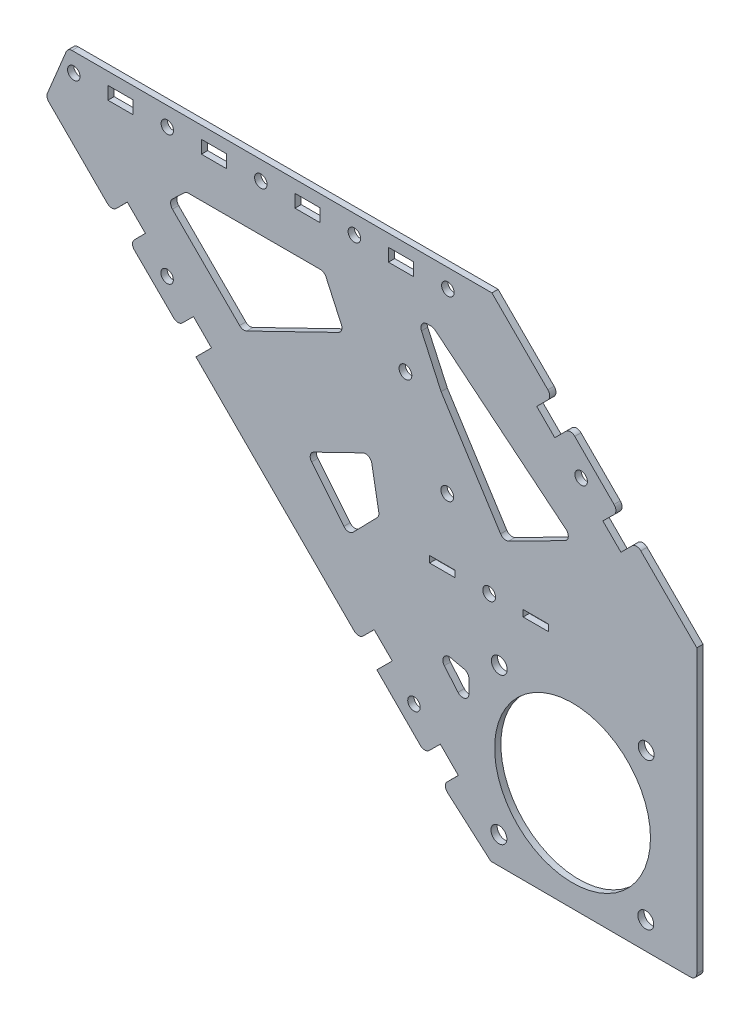
SolidWorks part; units mm, degrees
ref_plane "前视基准面" through (0, 0, 0) normal (0, 0, 1) x (1, 0, 0)
ref_plane "上视基准面" through (0, 0, 0) normal (0, 1, 0) x (1, 0, 0)
ref_plane "右视基准面" through (0, 0, 0) normal (1, 0, 0) x (0, 0, -1)
sketch "草图1" plane through (0, 0, 0) normal (0, 0, 1) x (1, 0, 0)
  line L261 (47.0274, 35.0547) -> (47.0274, 14.9275) construction
  line L315 (7.0453, -5.1539) -> (20.7932, -17.1527)
  line L316 (-52.9726, 134.9275) -> (-52.9726, 126.7057) construction
  line L332 (-112.9726, 134.9275) -> (-97.9726, 134.9275) construction
  line L334 (-42.0226, 136.9925) -> (-33.9226, 136.9925)
  line L335 (-42.0226, 136.9925) -> (-42.0226, 132.8625)
  line L336 (-42.0226, 132.8625) -> (-33.9226, 132.8625)
  line L337 (-33.9226, 136.9925) -> (-33.9226, 132.8625)
  line L338 (-42.0226, 136.9925) -> (-33.9226, 132.8625) construction
  line L339 (-42.0226, 132.8625) -> (-33.9226, 136.9925) construction
  line L389 (-114.8842, 140.9275) -> (21.1546, 140.9275)
  line L390 (-22.9726, 134.9275) -> (-22.9726, 144.5851) construction
  line L395 (-37.9726, 134.9275) -> (-7.9726, 134.9275) construction
  line L418 (86.9005, 75.1817) -> (21.1546, 140.9275) construction
  line L419 (-3.9226, 132.8625) -> (-12.0226, 136.9925) construction
  line L420 (-3.9226, 136.9925) -> (-12.0226, 132.8625) construction
  line L421 (7.0274, 134.9275) -> (-7.9726, 134.9275) construction
  line L422 (-12.0226, 136.9925) -> (-12.0226, 132.8625)
  line L423 (-3.9226, 132.8625) -> (-12.0226, 132.8625)
  line L424 (-3.9226, 136.9925) -> (-3.9226, 132.8625)
  line L443 (-3.9226, 136.9925) -> (-12.0226, 136.9925)
  line L444 (-102.0226, 136.9925) -> (-93.9226, 132.8625) construction
  line L445 (-102.0226, 132.8625) -> (-93.9226, 136.9925) construction
  line L447 (-67.9726, 134.9275) -> (-97.9726, 134.9275) construction
  line L448 (-104.2577, 114.6407) -> (-83.0445, 93.4275) construction
  line L449 (-63.9226, 132.8625) -> (-72.0226, 136.9925) construction
  line L483 (-63.9226, 136.9925) -> (-72.0226, 132.8625) construction
  line L515 (47.0274, 35.0547) -> (47.0274, 134.9275) construction
  line L516 (47.0274, 134.9275) -> (-52.9726, 134.9275) construction
  line L517 (-102.0226, 136.9925) -> (-93.9226, 136.9925)
  line L518 (-102.0226, 136.9925) -> (-102.0226, 132.8625)
  line L519 (-102.0226, 132.8625) -> (-93.9226, 132.8625)
  line L520 (-93.9226, 136.9925) -> (-93.9226, 132.8625)
  line L521 (-72.0226, 136.9925) -> (-72.0226, 132.8625)
  line L522 (-63.9226, 132.8625) -> (-72.0226, 132.8625)
  line L523 (-63.9226, 136.9925) -> (-63.9226, 132.8625)
  line L524 (-63.9226, 136.9925) -> (-72.0226, 136.9925)
  line L556 (21.4033, 132.1936) -> (81.3921, 72.2048) construction
  line L557 (54.0276, 108.0546) -> (35.0675, 89.0945) construction
  line L558 (42.8199, 112.2619) -> (35.5367, 116.5752) construction
  line L559 (56.7499, 95.3621) -> (62.5482, 89.5638)
  line L576 (56.7499, 95.3621) -> (58.2348, 96.847)
  line L577 (58.2348, 96.847) -> (64.0331, 91.0487) construction
  line L578 (62.5482, 89.5638) -> (64.0331, 91.0487)
  line L579 (56.7499, 95.3621) -> (64.0331, 91.0487) construction
  line L580 (58.2348, 96.847) -> (62.5482, 89.5638) construction
  line L581 (41.335, 110.777) -> (37.0216, 118.0602) construction
  line L582 (35.5367, 116.5752) -> (37.0216, 118.0602)
  line L583 (42.8199, 112.2619) -> (37.0216, 118.0602) construction
  line L584 (41.335, 110.777) -> (42.8199, 112.2619)
  line L585 (41.335, 110.777) -> (35.5367, 116.5752)
  line L586 (60.3915, 93.2054) -> (59.649, 92.4629) construction
  line L587 (39.1783, 114.4186) -> (38.4359, 113.6761) construction
  line L589 (20.2758, 56.9275) -> (5.2758, 56.9275) construction
  line L605 (-25.9364, 28.0074) -> (-21.7017, 32.2509) construction
  line L607 (-83.0445, 93.4275) -> (-87.254, 89.218) construction
  line L621 (-83.0445, 93.4275) -> (-61.8313, 72.2143) construction
  line L623 (73.2098, -17.3155) -> (86.9005, -17.3155)
  line L624 (23.5274, -8.5725) -> (70.5274, -8.5725) construction
  line L631 (-97.2991, 106.18) -> (-91.4837, 100.3989) construction
  line L632 (-82.9726, 134.9275) -> (-82.9726, 64.2144) construction
  line L633 (-97.2991, 106.18) -> (-95.8186, 107.6693)
  line L638 (-22.9726, 134.9275) -> (-22.9726, 124.8275) construction
  line L639 (86.9005, -17.3155) -> (86.9005, 75.1817)
  line L640 (20.2758, 56.9275) -> (20.2758, 57.5682) construction
  line L641 (9.3758, 55.8775) -> (1.1758, 55.8775)
  line L642 (9.3758, 55.8775) -> (9.3758, 57.9775)
  line L643 (9.3758, 57.9775) -> (1.1758, 57.9775)
  line L644 (1.1758, 55.8775) -> (1.1758, 57.9775)
  line L645 (9.3758, 55.8775) -> (1.1758, 57.9775) construction
  line L646 (9.3758, 57.9775) -> (1.1758, 55.8775) construction
  line L647 (31.1758, 57.9775) -> (39.3758, 55.8775) construction
  line L648 (31.1758, 55.8775) -> (39.3758, 57.9775) construction
  line L649 (39.3758, 55.8775) -> (39.3758, 57.9775)
  line L650 (31.1758, 57.9775) -> (39.3758, 57.9775)
  line L651 (31.1758, 55.8775) -> (31.1758, 57.9775)
  line L652 (31.1758, 55.8775) -> (39.3758, 55.8775)
  line L653 (-6.5853, 99.0995) -> (-61.8313, 72.2143) construction
  line L654 (-104.2577, 114.6407) -> (-82.9726, 134.9275) construction
  line L655 (-82.9726, 134.9275) -> (-22.9726, 134.9275) construction
  line L656 (-22.9726, 134.9275) -> (-6.5853, 99.0995) construction
  line L657 (-61.8313, 72.2143) -> (-104.2577, 114.6407) construction
  line L658 (-26.3178, 106.1787) -> (-58.7833, 90.3795)
  line L659 (-58.7833, 90.3795) -> (-82.7867, 114.383)
  line L660 (-82.7867, 114.383) -> (-76.9693, 119.9275)
  line L661 (-76.9693, 119.9275) -> (-32.6063, 119.9275)
  line L662 (-32.6063, 119.9275) -> (-26.3178, 106.1787)
  line L663 (70.9981, 82.5988) -> (20.2758, 56.9275) construction
  line L664 (70.9981, 82.5988) -> (7.0274, 134.9275) construction
  line L665 (7.0274, 134.9275) -> (-22.9726, 134.9275) construction
  line L667 (47.3104, 85.1802) -> (24.9135, 73.8449)
  line L668 (4.8626, 105.3248) -> (24.9135, 73.8449)
  line L669 (-2.7313, 121.9275) -> (4.8626, 105.3248)
  line L670 (2.3877, 121.9275) -> (-2.7313, 121.9275)
  line L671 (47.3104, 85.1802) -> (2.3877, 121.9275)
  line L672 (1.1758, 55.8775) -> (-6.5853, 99.0995) construction
  line L673 (-61.8313, 72.2143) -> (-25.9364, 28.0074) construction
  line L674 (-25.9364, 28.0074) -> (1.1758, 55.8775) construction
  line L675 (-14.9502, 60.8125) -> (-17.8458, 76.9378)
  line L676 (-17.8458, 76.9378) -> (-38.2729, 66.997)
  line L677 (-38.2729, 66.997) -> (-24.9253, 50.5586)
  line L678 (-24.9253, 50.5586) -> (-14.9502, 60.8125)
  line L679 (23.8026, -6.8752) -> (23.8026, 39.6213) construction
  line L680 (23.8026, 39.6213) -> (-24.9253, 50.5586) construction
  line L681 (-24.9253, 50.5586) -> (23.8026, -6.8752) construction
  line L682 (2.0144, 34.263) -> (13.8026, 20.3686)
  line L683 (13.8026, 20.3686) -> (13.8026, 31.617)
  line L684 (13.8026, 31.617) -> (2.0144, 34.263)
  line L685 (23.5274, -8.5725) -> (23.5274, 38.4275) construction
  line L686 (23.5274, 38.4275) -> (70.5274, 38.4275) construction
  line L687 (70.5274, -8.5725) -> (70.5274, 38.4275) construction
  line L688 (23.5274, -8.5725) -> (70.5274, 38.4275) construction
  line L689 (23.5274, 38.4275) -> (70.5274, -8.5725) construction
  line L690 (-91.4837, 100.3989) -> (-90.0031, 101.8883)
  line L691 (-95.8186, 107.6693) -> (-90.0031, 101.8883)
  line L692 (-97.2991, 106.18) -> (-90.0031, 101.8883) construction
  line L693 (-91.4837, 100.3989) -> (-95.8186, 107.6693) construction
  line L694 (-76.0731, 84.9884) -> (-68.8027, 80.6535) construction
  line L695 (-70.292, 79.1729) -> (-74.5838, 86.4689) construction
  line L696 (-68.8027, 80.6535) -> (-74.5838, 86.4689)
  line L697 (-76.0731, 84.9884) -> (-74.5838, 86.4689)
  line L698 (-70.292, 79.1729) -> (-68.8027, 80.6535)
  line L699 (-70.292, 79.1729) -> (-76.0731, 84.9884) construction
  line L700 (-70.292, 79.1729) -> (-73.7905, 75.6745)
  line L701 (-76.0731, 84.9884) -> (-79.5259, 81.5356)
  line L702 (-91.4837, 100.3989) -> (-94.9717, 96.8901)
  line L703 (-97.2991, 106.18) -> (-100.7786, 102.6798)
  line L704 (-121.9553, 123.8565) -> (-100.7786, 102.6798)
  line L705 (-94.9717, 96.8901) -> (-87.254, 89.218)
  line L706 (-87.254, 89.218) -> (-79.5259, 81.5356)
  line L708 (37.0216, 118.0602) -> (40.5218, 121.5603)
  line L709 (40.5218, 121.5603) -> (21.1546, 140.9275)
  line L710 (42.8199, 112.2619) -> (46.3201, 115.7621)
  line L711 (46.3201, 115.7621) -> (54.0276, 108.0546)
  line L712 (54.0276, 108.0546) -> (61.7717, 100.3104)
  line L713 (61.7717, 100.3104) -> (58.2348, 96.847)
  line L714 (64.0331, 91.0487) -> (67.5333, 94.5489)
  line L715 (67.5333, 94.5489) -> (86.9005, 75.1817)
  line L716 (20.7932, -17.1527) -> (73.2098, -17.3155)
  line L717 (-6.5853, 99.0995) -> (20.2758, 56.9275) construction
  line L719 (81.3921, -8.4453) -> (81.3921, 72.2048) construction
  line L721 (-121.9553, 123.8565) -> (-114.8842, 140.9275)
  line L722 (80.2921, 53.1048) -> (82.4921, 53.1048) construction
  line L723 (80.2921, 53.1048) -> (80.2921, 61.3048) construction
  line L724 (80.2921, 61.3048) -> (82.4921, 61.3048) construction
  line L725 (82.4921, 53.1048) -> (82.4921, 61.3048) construction
  line L726 (80.2921, 53.1048) -> (82.4921, 61.3048) construction
  line L727 (80.2921, 61.3048) -> (82.4921, 53.1048) construction
  line L728 (80.2921, 2.4547) -> (82.4921, 2.4547) construction
  line L729 (80.2921, 2.4547) -> (80.2921, 10.6547) construction
  line L730 (80.2921, 10.6547) -> (82.4921, 10.6547) construction
  line L731 (82.4921, 2.4547) -> (82.4921, 10.6547) construction
  line L732 (80.2921, 2.4547) -> (82.4921, 10.6547) construction
  line L733 (80.2921, 10.6547) -> (82.4921, 2.4547) construction
  line L734 (-6.5853, 99.0995) -> (20.2758, 56.9275) construction
  line L735 (-47.6875, 49.5886) -> (-42.0122, 55.2639) construction
  line L736 (3.1229, 5.7924) -> (10.3932, 1.4575) construction
  line L737 (8.9039, -0.023) -> (4.6122, 7.2729) construction
  line L738 (8.9039, -0.023) -> (3.1229, 5.7924) construction
  line L739 (17.3646, -6.9816) -> (-3.8486, 14.2316) construction
  line L740 (-0.386, 2.3044) -> (-8.058, 10.0221)
  line L741 (-21.6016, 23.4856) -> (-73.7905, 75.6745)
  line L742 (8.9039, -0.023) -> (5.4037, -3.5025)
  line L743 (3.1229, 5.7924) -> (-0.386, 2.3044)
  line L744 (10.3932, 1.4575) -> (4.6122, 7.2729)
  line L745 (3.1229, 5.7924) -> (4.6122, 7.2729)
  line L746 (8.9039, -0.023) -> (10.3932, 1.4575)
  line L747 (-18.1031, 26.984) -> (-12.2877, 21.203) construction
  line L748 (-18.1031, 26.984) -> (-10.8072, 22.6923) construction
  line L749 (-12.2877, 21.203) -> (-16.6226, 28.4734) construction
  line L750 (-25.0618, 35.4448) -> (17.3646, -6.9816) construction
  line L751 (-3.8486, 14.2316) -> (-25.0618, 35.4448) construction
  line L752 (5.4037, -3.5025) -> (7.0453, -5.1539)
  line L753 (-6.5853, 99.0995) -> (-6.5853, 105.0995) construction
  line L754 (-8.058, 10.0221) -> (-15.7405, 17.7502)
  line L755 (-12.2877, 21.203) -> (-15.7405, 17.7502)
  line L756 (-18.1031, 26.984) -> (-21.6016, 23.4856)
  line L757 (-18.1031, 26.984) -> (-16.6226, 28.4734)
  line L758 (-12.2877, 21.203) -> (-10.8072, 22.6923)
  line L759 (-16.6226, 28.4734) -> (-10.8072, 22.6923)
  circle A39 centre (-52.9726, 134.9275) radius 2
  circle A42 centre (47.0274, 14.9275) radius 25
  circle A49 centre (-22.9726, 134.9275) radius 2
  circle A69 centre (7.0274, 134.9275) radius 2
  circle A92 centre (-112.9726, 134.9275) radius 2
  circle A93 centre (-82.9726, 134.9275) radius 2
  circle A98 centre (49.7849, 103.812) radius 2
  arc A115 (-114.8842, 140.9275) -> (-121.9553, 123.8565) centre (-114.8842, 130.9275) ccw construction
  circle A116 centre (-83.0445, 93.4275) radius 2
  circle A121 centre (20.2758, 56.9275) radius 2.05
  circle A122 centre (-6.5853, 99.0995) radius 2.05 construction
  circle A123 centre (70.5274, -8.5725) radius 2.55
  circle A124 centre (23.4002, -8.4453) radius 2.55
  circle A125 centre (23.5274, 38.682) radius 2.55
  circle A126 centre (70.6546, 38.5547) radius 2.55
  circle A127 centre (81.3921, 72.2048) radius 2.05 construction
  circle A128 centre (81.3921, -8.4453) radius 2.05 construction
  circle A129 centre (81.3921, 42.2048) radius 2.05 construction
  circle A130 centre (6.8453, 78.0135) radius 2.05
  circle A131 centre (-3.8486, 14.2316) radius 2
  circle A132 centre (-6.5853, 105.0995) radius 2.05
  point P5 (210.9534, 218.4629)
  point P6 (288.6284, 218.4629)
  point P51 (-93.6511, 104.0341)
  point P54 (-105.4726, 134.9275)
  point P60 (60.3915, 93.2054)
  point P83 (-93.6511, 104.0341)
  point P98 (81.3921, 57.2048)
  point P115 (47.016, -39.6917)
  point P147 (-72.4379, 82.8209)
  point P152 (81.3921, 6.5547)
  point P173 (6.758, 3.625)
  point P183 (-14.4552, 24.8382)
  dimension "D3" = 50
  dimension "D5" = 4
  dimension "D4" = 47
  dimension "D6" = 15
  dimension "D7" = 2.1
  dimension "D12" = 4
  dimension "D19" = 29.4043
  dimension "D20" = 2.2
  dimension "D22" = 4
  dimension "D8" = 30
  dimension "D28" = 8.2
  dimension "D26" = 10
  dimension "D17" = 10.1
  dimension "D29" = 42
  dimension "D30" = 15
  dimension "D31" = 80.6501
  dimension "D18" = 8.2
  dimension "D15" = 8.2
  dimension "D27" = 30
  dimension "D40" = 56
  dimension "D41" = 8.2
  dimension "D9" = 15
  dimension "D10" = 15
  dimension "D11" = 8.1
  dimension "D13" = 4.13
  dimension "D14" = 6
  dimension "D16" = 41.5
  dimension "D21" = 6
  dimension "D23" = 15
  dimension "D24" = 15
  dimension "D25" = 2.1
  dimension "D32" = 8.2
  dimension "D33" = 2.1
  dimension "D34" = 120
  dimension "D35" = 70
  dimension "D36" = 15
  dimension "D37" = 13
  dimension "D38" = 15
  dimension "D39" = 10
extrude "凸台-拉伸1" add sketch "草图1" along normal blind 2
fillet "圆角2" radius 2 29 edges at (-76.9693, 119.9275, 1) (-82.7867, 114.383, 1) (-32.6063, 119.9275, 1) (-26.3178, 106.1787, 1) (-58.7833, 90.3795, 1) (-17.8458, 76.9378, 1) (-14.9502, 60.8125, 1) (-24.9253, 50.5586, 1) (-38.2729, 66.997, 1) (47.3104, 85.1802, 1) (24.9135, 73.8449, 1) (2.3877, 121.9275, 1) (-2.7313, 121.9275, 1) (13.8026, 31.617, 1) (2.0144, 34.263, 1) (13.8026, 20.3686, 1) (86.9005, -17.3155, 1) (-100.7786, 102.6798, 1) (-94.9717, 96.8901, 1) (-79.5259, 81.5356, 1) (67.5333, 94.5489, 1) (61.7717, 100.3104, 1) (46.3201, 115.7621, 1) (40.5218, 121.5603, 1) (-114.8842, 140.9275, 1) (-121.9553, 123.8565, 1) (5.4037, -3.5025, 1) (-0.386, 2.3044, 1) (-21.6016, 23.4856, 1)
